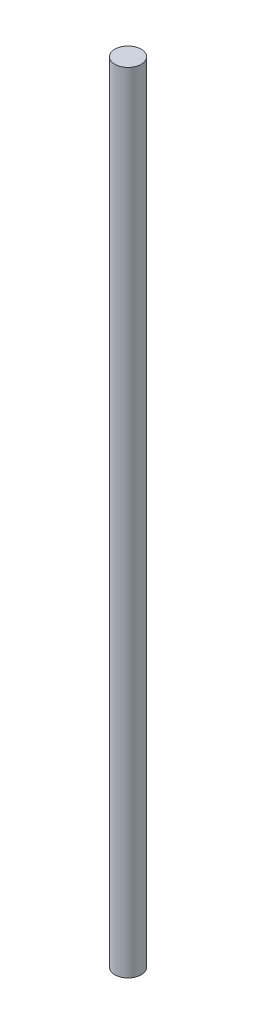
SolidWorks part; units mm, degrees
material "6061 Сплав"
ref_plane "Спереди" through (0, 0, 0) normal (0, 0, 1) x (1, 0, 0)
ref_plane "Сверху" through (0, 0, 0) normal (0, 1, 0) x (1, 0, 0)
ref_plane "Справа" through (0, 0, 0) normal (1, 0, 0) x (0, 0, -1)
sketch "Эскиз1" plane through (0, 0, 0) normal (0, 1, 0) x (1, 0, 0)
  circle A0 centre (0, 0) radius 1.5
  dimension "D1" = 3
extrude "Бобышка-Вытянуть1" add sketch "Эскиз1" along normal blind 90
